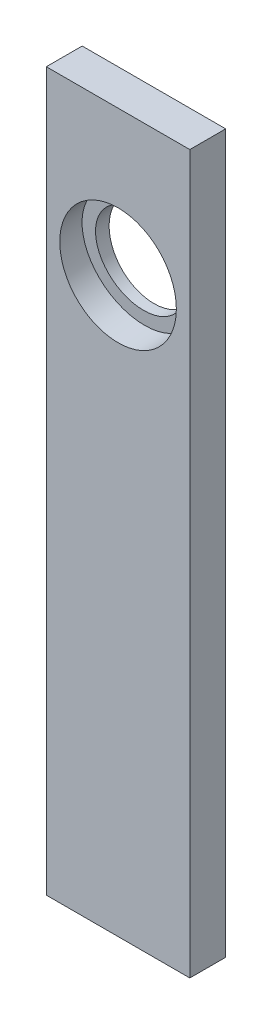
SolidWorks part; units mm, degrees
ref_plane "Front Plane" through (0, 0, 0) normal (0, 0, 1) x (1, 0, 0)
ref_plane "Top Plane" through (0, 0, 0) normal (0, 1, 0) x (1, 0, 0)
ref_plane "Right Plane" through (0, 0, 0) normal (1, 0, 0) x (0, 0, -1)
sketch "Sketch1" plane through (0, 0, 0) normal (0, 0, 1) x (1, 0, 0)
  line L1 (-40, 200) -> (40, 200)
  line L2 (-40, 200) -> (-40, -200)
  line L3 (-40, -200) -> (40, -200)
  line L4 (40, 200) -> (40, -200)
  line L5 (-40, 200) -> (40, -200) construction
  line L6 (-40, -200) -> (40, 200) construction
  point P0 (0, 0)
  dimension "D1" = 400
  dimension "D2" = 80
extrude "Boss-Extrude1" add sketch "Sketch1" along normal blind 20
sketch "Sketch2" plane through (0, 0, 20) normal (0, 0, 1) x (1, 0, 0)
  line L0 (0, -200) -> (0, 120)
  line L1 (-40, -200) -> (40, -200) construction
  dimension "D1" = 320
ref_plane "Plane1" through (0, 120, 0) normal (0, 1, 0) x (1, 0, 0)
sketch "Sketch3" plane through (0, 120, 0) normal (0, 1, 0) x (1, 0, 0)
  line L0 (0, -20) -> (0, 0)
  line L2 (0, -7.5) -> (15.3391, -7.5) construction
ref_plane "Plane3" through (0, 0.062, -0.8869) normal (0, -0.0698, 0.9976) x (1, 0, 0)
sketch "Sketch4" plane through (0, 0.062, -0.8869) normal (0, -0.0698, 0.9976) x (1, 0, 0)
  line L0 (0, 121.1028) -> (0, 119.7077) construction
  circle A0 centre (0, 120.4053) radius 32.5
  dimension "D1" = 65
extrude "Cut-Extrude4" cut sketch "Sketch4" along normal through all
sketch "Sketch6" plane through (0, 0.062, -0.8869) normal (0, -0.0698, 0.9976) x (1, 0, 0)
  circle A1 centre (0, 120.4053) radius 25
  dimension "D1" = 50
extrude "Cut-Extrude6" cut sketch "Sketch6" against normal through all
